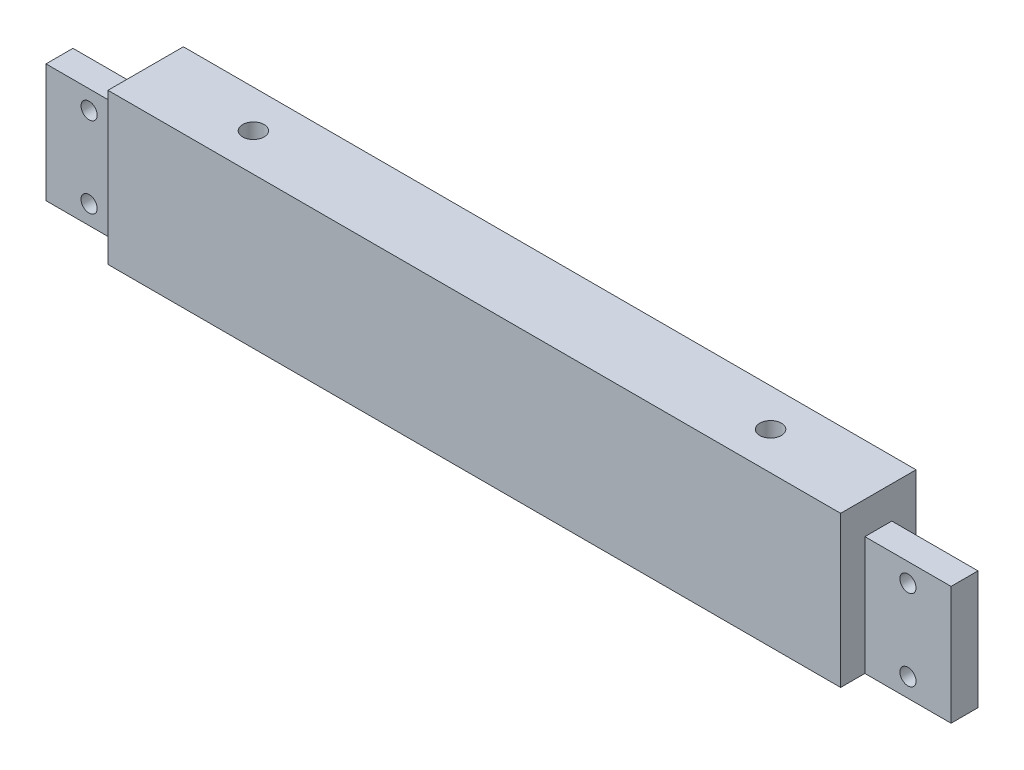
SolidWorks part; units mm, degrees
ref_plane "Front Plane" through (0, 0, 0) normal (0, 0, 1) x (1, 0, 0)
ref_plane "Top Plane" through (0, 0, 0) normal (0, 1, 0) x (1, 0, 0)
ref_plane "Right Plane" through (0, 0, 0) normal (1, 0, 0) x (0, 0, -1)
sketch "Sketch1" plane through (0, 0, 0) normal (0, 0, 1) x (1, 0, 0)
  line L1 (215.9, 44.45) -> (-215.9, 44.45)
  line L2 (215.9, 44.45) -> (215.9, -44.45)
  line L3 (215.9, -44.45) -> (-215.9, -44.45)
  line L4 (-215.9, 44.45) -> (-215.9, -44.45)
  line L5 (215.9, 44.45) -> (-215.9, -44.45) construction
  line L6 (215.9, -44.45) -> (-215.9, 44.45) construction
  point P0 (0, 0)
  dimension "D1" = 88.9
  dimension "D2" = 431.8
extrude "Boss-Extrude1" add sketch "Sketch1" along normal mid plane 44.45
sketch "Sketch2" plane through (215.9, 0, 0) normal (1, 0, 0) x (0, 0, -1)
  line L0 (-22.225, -44.45) -> (22.225, -44.45) construction
  line L1 (7.9375, 25.4) -> (-7.9375, 25.4)
  line L2 (7.9375, 25.4) -> (7.9375, -44.45)
  line L3 (7.9375, -44.45) -> (-7.9375, -44.45)
  line L4 (-7.9375, 25.4) -> (-7.9375, -44.45)
  line L5 (7.9375, 25.4) -> (-7.9375, -44.45) construction
  line L6 (7.9375, -44.45) -> (-7.9375, 25.4) construction
  line L7 (22.225, -44.45) -> (22.225, 44.45) construction
  point P0 (0, 0)
  point P6 (0, 0)
  point P7 (0, 0)
  dimension "D1" = 15.875
  dimension "D2" = 69.85
  dimension "D3" = 14.2875
extrude "Boss-Extrude2" add sketch "Sketch2" along normal blind 50.8 contours L4 L3 L2 L1
sketch "Sketch3" plane through (0, 0, 7.9375) normal (0, 0, 1) x (1, 0, 0)
  line L0 (266.7, 25.4) -> (215.9, -44.45) construction
  line L1 (241.3, -9.525) -> (241.3, 25.4) construction
  line L2 (266.7, 25.4) -> (215.9, 25.4) construction
  circle A0 centre (241.3, 14.2875) radius 4.7625
  circle A1 centre (241.3, -33.3375) radius 4.7625
  point P12 (0, 0)
  dimension "D1" = 9.525
  dimension "D2" = 23.8125
  dimension "D3" = 23.8125
extrude "Cut-Extrude1" cut sketch "Sketch3" against normal through all contours A0 | A1
mirror "Mirror1" about plane through (0, 0, 0) normal (1, 0, 0) of "Boss-Extrude2", "Cut-Extrude1"
sketch "Sketch5" plane through (0, 44.45, 0) normal (0, 1, 0) x (1, 0, 0)
  line L0 (-215.9, 0) -> (215.9, 0) construction
  line L1 (-215.9, -22.225) -> (-215.9, 22.225) construction
  line L2 (215.9, -22.225) -> (215.9, 22.225) construction
  circle A0 centre (-152.4, 0) radius 6.35
  circle A1 centre (152.4, 0) radius 6.35
  dimension "D1" = 12.7
  dimension "D2" = 63.5
  dimension "D3" = 304.8
extrude "Cut-Extrude3" cut sketch "Sketch5" against normal through all
